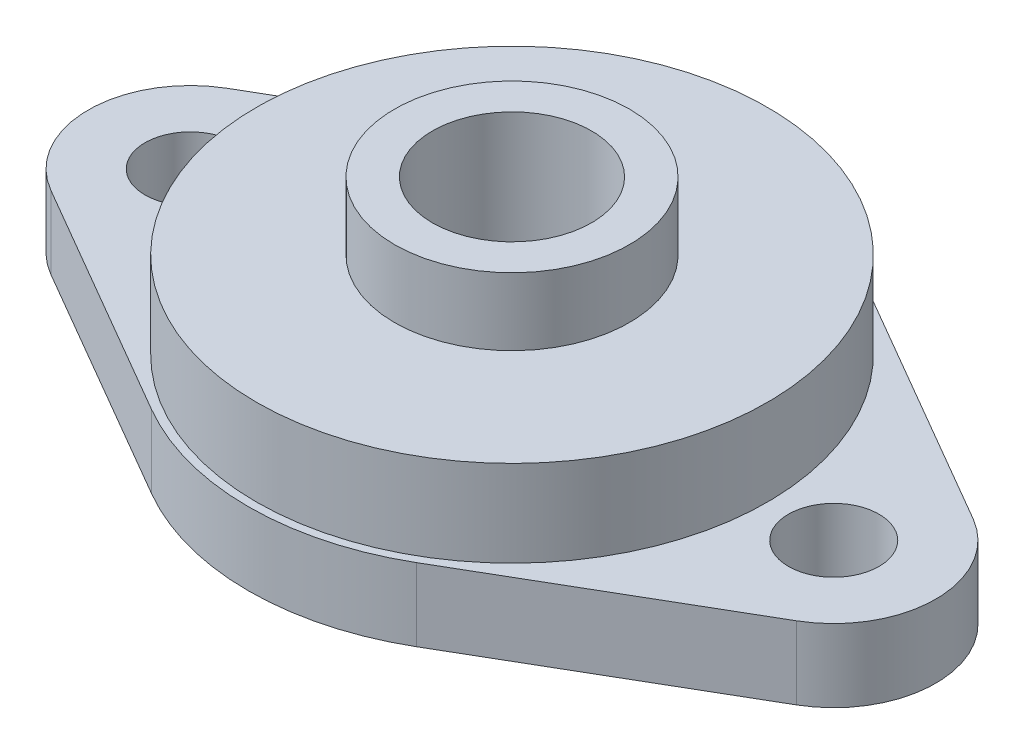
SolidWorks part; units mm, degrees
ref_plane "Front Plane" through (0, 0, 0) normal (0, 0, 1) x (1, 0, 0)
ref_plane "Top Plane" through (0, 0, 0) normal (0, 1, 0) x (1, 0, 0)
ref_plane "Right Plane" through (0, 0, 0) normal (1, 0, 0) x (0, 0, -1)
sketch "Sketch1" plane through (0, 0, 0) normal (0, 1, 0) x (1, 0, 0)
  line L1 (0, 0) -> (0, 64.2315) construction
  line L2 (0, -42.6093) -> (0, 42.6093) construction
  line L3 (0, 0) -> (-11.035, 0) construction
  line L4 (-20.306, 0) -> (20.306, 0) construction
  line L8 (-16.16, -10.0293) -> (-16.16, -5.9264) construction
  line L9 (-6.6487, 11.4496) -> (-18.7336, 4.432)
  line L11 (-6.6487, -11.4496) -> (-18.7336, -4.432)
  line L12 (-13.885, 0) -> (-23.68, 0) construction
  line L13 (-16.16, 5.125) -> (-16.16, 10.7839) construction
  line L14 (-16.16, -2.275) -> (-16.16, 2.275) construction
  line L15 (0, 13.24) -> (0, -13.24)
  circle A6 centre (-16.16, 0) radius 2.275
  arc A7 (-18.7336, 4.432) -> (-18.7336, -4.432) centre (-16.16, 0) ccw
  arc A8 (-6.6487, -11.4496) -> (0, -13.24) centre (0, 0) ccw
  arc A9 (0, 13.24) -> (-6.6487, 11.4496) centre (0, 0) ccw
  dimension "D1" = 26.48
  dimension "D3" = 4.55
  dimension "D5" = 2.85
  dimension "D2" = 23.68
  dimension "D4" = 16.16
sketch "Sketch8" plane through (0, 0, 0) normal (0, 1, 0) x (1, 0, 0)
  circle A0 centre (0, 0) radius 12.835
  dimension "D1" = 25.67
extrude "Boss-Extrude4" add sketch "Sketch1" along normal blind 3.66
mirror "Mirror2" about plane through (0, 0, 0) normal (1, 0, 0) of "Boss-Extrude4"
extrude "Boss-Extrude5" add sketch "Sketch8" along normal blind 8
sketch "Sketch9" plane through (0, 0, 0) normal (0, 1, 0) x (1, 0, 0)
  circle A0 centre (0, 0) radius 5.9
  dimension "D1" = 11.8
extrude "Boss-Extrude6" add sketch "Sketch9" along normal blind 11.39
sketch "Sketch10" plane through (0, 11.39, 0) normal (0, 1, 0) x (1, 0, 0)
  circle A0 centre (0, 0) radius 4
  dimension "D1" = 8
extrude "Cut-Extrude3" cut sketch "Sketch10" against normal through all
